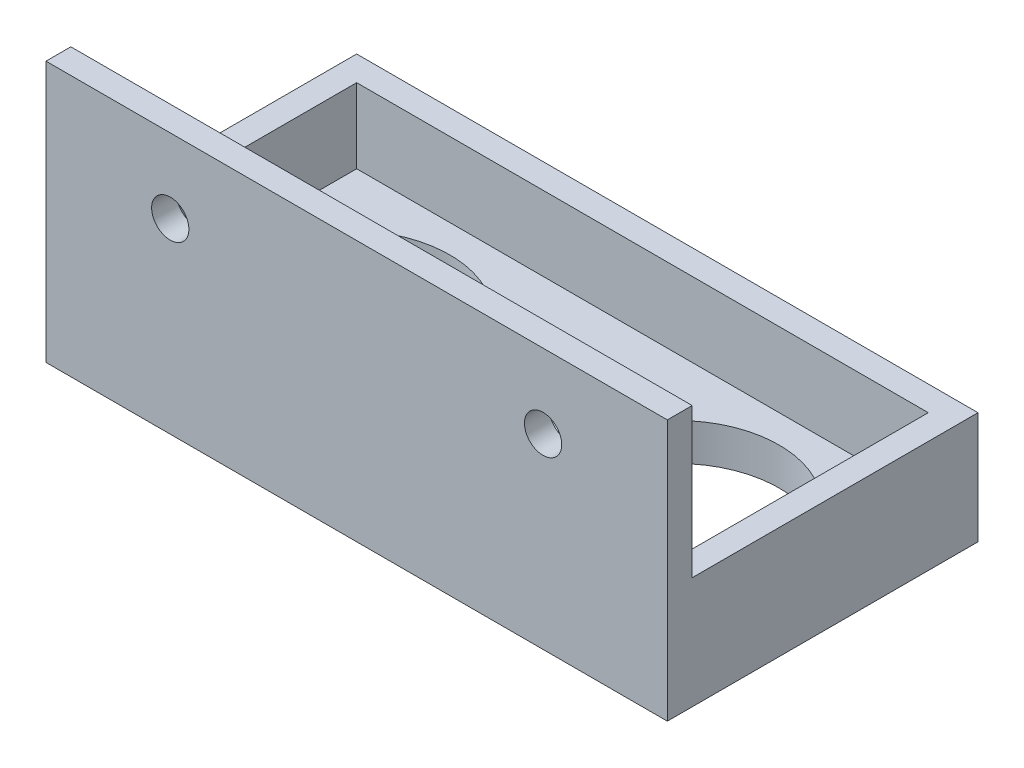
SolidWorks part; units mm, degrees
ref_plane "Front" through (0, 0, 0) normal (0, 0, 1) x (1, 0, 0)
ref_plane "Top" through (0, 0, 0) normal (0, 1, 0) x (1, 0, 0)
ref_plane "Right" through (0, 0, 0) normal (1, 0, 0) x (0, 0, -1)
sketch "Sketch1" plane through (0, 0, 0) normal (0, 1, 0) x (1, 0, 0)
  line L0 (-25, 12.5) -> (25, 12.5)
  line L1 (-25, 12.5) -> (-25, -12.5)
  line L2 (25, 12.5) -> (25, -12.5)
  line L3 (-25, -12.5) -> (25, -12.5)
  line L8 (-25, 12.5) -> (25, -12.5) construction
  line L9 (-25, -12.5) -> (0, 0) construction
  dimension "D1" = 50
  dimension "D2" = 25
extrude "Boss-Extrude2" add sketch "Sketch1" along normal blind 3 contours L0 L2 L3 L1
sketch "Sketch3" plane through (0, 3, 0) normal (0, 1, 0) x (1, 0, 0)
  line L0 (-5, 0) -> (5, 0) construction
  circle A0 centre (13.25, 0) radius 8.25
  circle A1 centre (-13.25, 0) radius 8.25
  dimension "D1" = 16.5
  dimension "D2" = 10
extrude "Cut-Extrude2" cut sketch "Sketch3" against normal through all
sketch "Sketch6" plane through (0, 3, 0) normal (0, 1, 0) x (1, 0, 0)
  line L14 (23, -10.5) -> (23, 10.5)
  line L15 (-23, -10.5) -> (23, -10.5)
  line L16 (-23, 10.5) -> (-23, -10.5)
  line L17 (23, 10.5) -> (-23, 10.5)
  line L18 (23, -10.5) -> (23, 10.5)
  line L19 (-23, -10.5) -> (23, -10.5)
  line L20 (-23, 10.5) -> (-23, -10.5)
  line L21 (23, 10.5) -> (-23, 10.5)
  line M7 (-25, 12.5) -> (-25, -12.5)
  line M8 (-25, -12.5) -> (25, -12.5)
  line M9 (25, -12.5) -> (25, 12.5)
  line M10 (25, 12.5) -> (-25, 12.5)
  dimension "D1" = 2
extrude "Boss-Extrude3" add sketch "Sketch6" along normal blind 6 contours L21 L18 L19 L20 M10 M7 M8 M9
sketch "Sketch7" plane through (0, 9, 0) normal (0, 1, 0) x (1, 0, 0)
  line L0 (-25, -12.5) -> (25, -12.5)
  line L1 (25, -10.5) -> (-25, -10.5)
  line L2 (25, -12.5) -> (25, 12.5) construction
  line L3 (-25, 12.5) -> (-25, -12.5) construction
  line L4 (-25, -10.5) -> (-25, -12.5)
  line L5 (25, -10.5) -> (25, -12.5)
  dimension "D1" = 2
extrude "Boss-Extrude4" add sketch "Sketch7" along normal blind 12
sketch "Sketch8" plane through (0, 0, 10.5) normal (0, 0, -1) x (-1, 0, 0)
  line L0 (-25, 16) -> (25, 16) construction
  line L4 (-25, 21) -> (25, 21) construction
  dimension "D1" = 5
sketch "Sketch9" plane through (0, 0, 10.5) normal (0, 0, -1) x (-1, 0, 0)
  circle A0 centre (-15, 15.0267) radius 1.5
  circle A1 centre (15, 15.0267) radius 1.5
  dimension "D1" = 10
  dimension "D3" = 3
  dimension "D2" = 10
extrude "Cut-Extrude3" cut sketch "Sketch9" against normal through all
